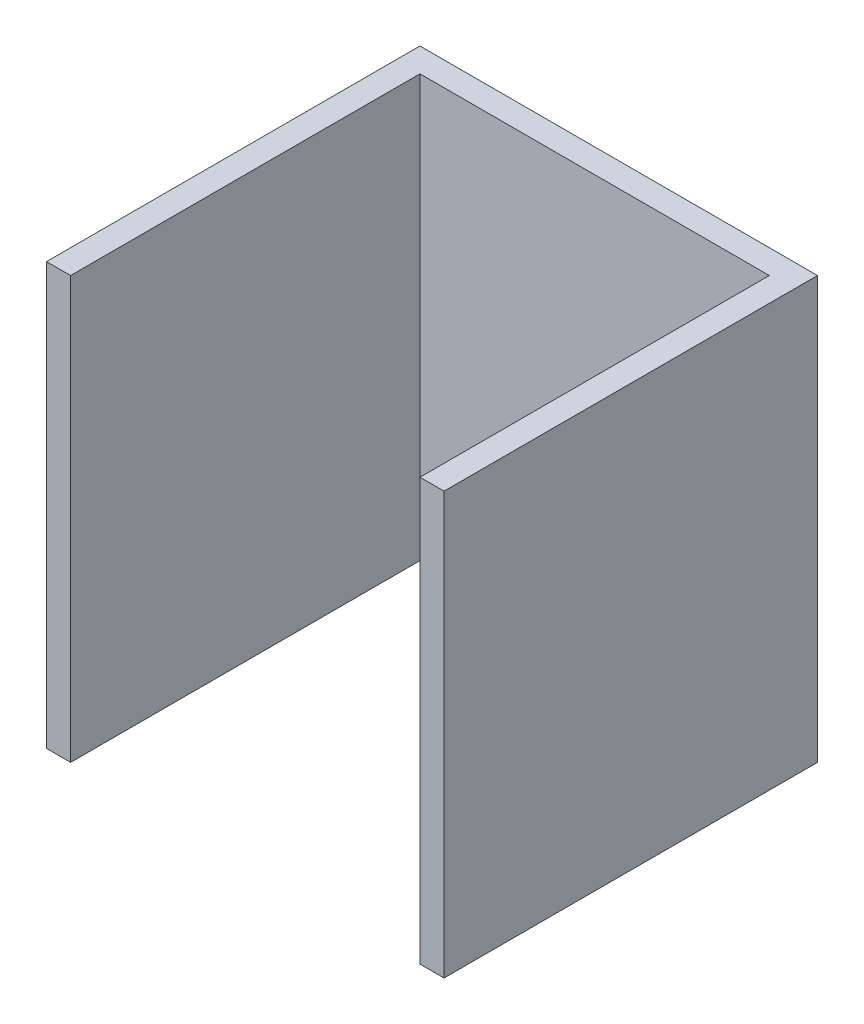
SolidWorks part; units mm, degrees
ref_plane "Front Plane" through (0, 0, 0) normal (0, 0, 1) x (1, 0, 0)
ref_plane "Top Plane" through (0, 0, 0) normal (0, 1, 0) x (1, 0, 0)
ref_plane "Right Plane" through (0, 0, 0) normal (1, 0, 0) x (0, 0, -1)
sketch "Sketch1" plane through (0, 0, 0) normal (0, 1, 0) x (1, 0, 0)
  line L0 (26.69, 5.3011) -> (28.69, 5.3011)
  line L1 (-4.31, 36.3011) -> (28.69, 36.3011)
  line L2 (-4.31, 36.3011) -> (-4.31, 5.3011)
  line L3 (-4.31, 5.3011) -> (-2.31, 5.3011)
  line L4 (28.69, 36.3011) -> (28.69, 5.3011)
  line L6 (-2.31, 5.3011) -> (-2.31, 34.3011)
  line L7 (-2.31, 34.3011) -> (26.69, 34.3011)
  line L8 (26.69, 5.3011) -> (26.69, 34.3011)
  dimension "D1" = 2
  dimension "D2" = 2
  dimension "D3" = 29
  dimension "D4" = 29
extrude "Boss-Extrude1" add sketch "Sketch1" along normal blind 35
